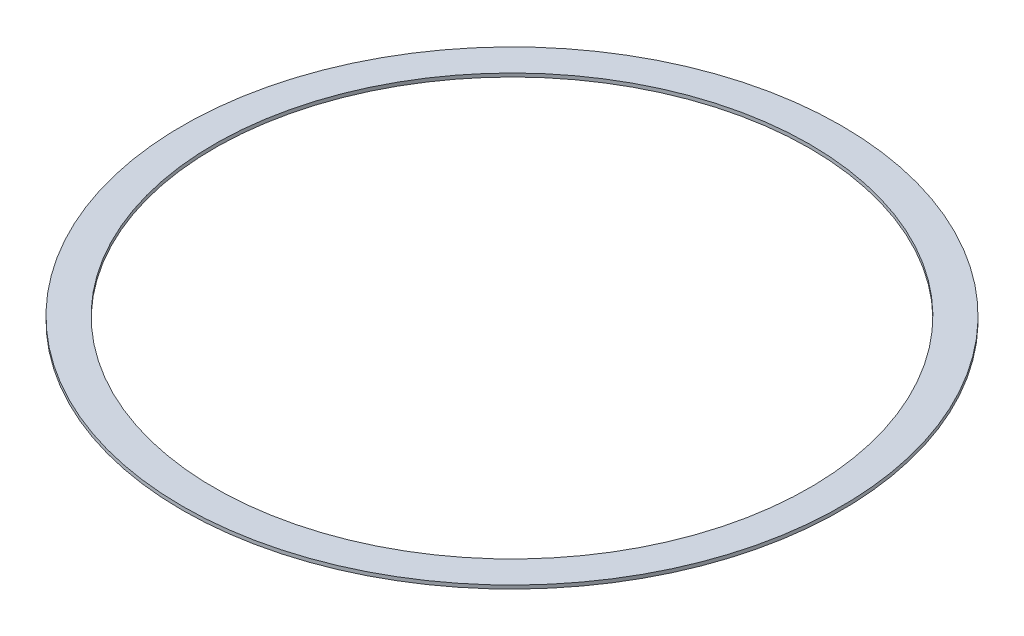
SolidWorks part; units mm, degrees
ref_plane "Front Plane" through (0, 0, 0) normal (0, 0, 1) x (1, 0, 0)
ref_plane "Top Plane" through (0, 0, 0) normal (0, 1, 0) x (1, 0, 0)
ref_plane "Right Plane" through (0, 0, 0) normal (1, 0, 0) x (0, 0, -1)
sketch "Sketch1" plane through (0, 0, 0) normal (0, 1, 0) x (1, 0, 0)
  circle A0 centre (0, 0) radius 72.0725
  circle A1 centre (0, 0) radius 65.0875
  point P4 (0, 0)
extrude "Boss-Extrude1" add sketch "Sketch1" along normal blind 0.762 contours A0 | A1
